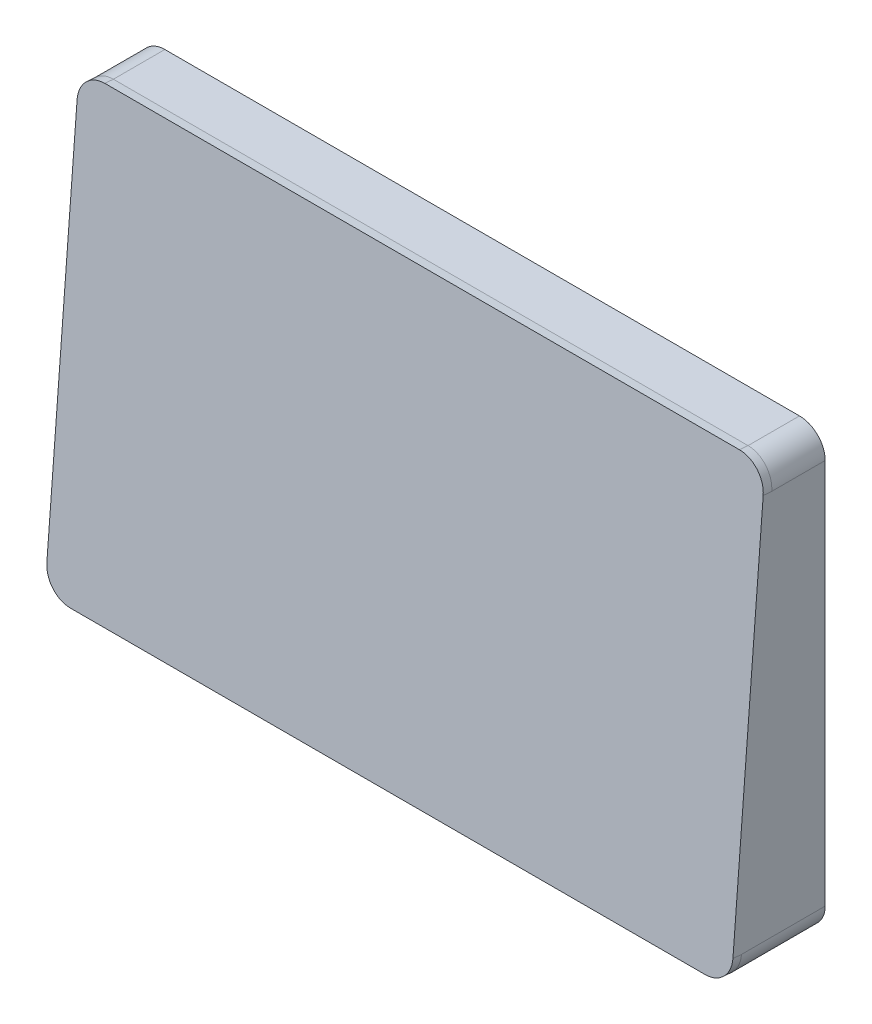
SolidWorks part; units mm, degrees
ref_plane "Front Plane" through (0, 0, 0) normal (0, 0, 1) x (1, 0, 0)
ref_plane "Top Plane" through (0, 0, 0) normal (0, 1, 0) x (1, 0, 0)
ref_plane "Right Plane" through (0, 0, 0) normal (1, 0, 0) x (0, 0, -1)
sketch "Sketch1" plane through (0, 0, 0) normal (0, 0, 1) x (1, 0, 0)
  line L0 (3.325, 90.1) -> (3.325, 0.1) construction
  line L1 (0.325, -2.9) -> (-147.675, -2.9) construction
  line L2 (-150.675, 0.1) -> (-150.675, 90.1) construction
  line L3 (-147.675, 93.1) -> (0.325, 93.1) construction
  line L4 (3.325, 90.1) -> (3.325, 0.1)
  line L5 (0.325, -2.9) -> (-147.675, -2.9)
  line L6 (-150.675, 0.1) -> (-150.675, 90.1)
  line L7 (-147.675, 93.1) -> (0.325, 93.1)
  line L8 (-153.675, 0.1) -> (-153.675, 90.1)
  line L9 (0.325, -5.9) -> (-147.675, -5.9)
  line L10 (6.325, 90.1) -> (6.325, 0.1)
  line L11 (-147.675, 96.1) -> (0.325, 96.1)
  arc A0 (3.325, 90.1) -> (0.325, 93.1) centre (0.325, 90.1) ccw construction
  arc A1 (0.325, -2.9) -> (3.325, 0.1) centre (0.325, 0.1) ccw construction
  arc A2 (-150.675, 0.1) -> (-147.675, -2.9) centre (-147.675, 0.1) ccw construction
  arc A3 (-147.675, 93.1) -> (-150.675, 90.1) centre (-147.675, 90.1) ccw construction
  arc A4 (3.325, 90.1) -> (0.325, 93.1) centre (0.325, 90.1) ccw
  arc A5 (0.325, -2.9) -> (3.325, 0.1) centre (0.325, 0.1) ccw
  arc A6 (-150.675, 0.1) -> (-147.675, -2.9) centre (-147.675, 0.1) ccw
  arc A7 (-147.675, 93.1) -> (-150.675, 90.1) centre (-147.675, 90.1) ccw
  arc A8 (-147.675, 96.1) -> (-153.675, 90.1) centre (-147.675, 90.1) ccw
  arc A9 (-153.675, 0.1) -> (-147.675, -5.9) centre (-147.675, 0.1) ccw
  arc A10 (0.325, -5.9) -> (6.325, 0.1) centre (0.325, 0.1) ccw
  arc A11 (6.325, 90.1) -> (0.325, 96.1) centre (0.325, 90.1) ccw
  dimension "D1" = 3
extrude "Boss-Extrude1" add sketch "Sketch1" along normal blind 20
sketch "Sketch2" plane through (6.325, 0, 0) normal (1, 0, 0) x (0, 0, -1)
  line L0 (-20, 96.1) -> (-12, 96.1)
  line L1 (-20, 96.1) -> (0, 96.1) construction
  line L2 (-12, 96.1) -> (-20, -5.9)
  line L3 (-20, -5.9) -> (-20, 96.1)
  dimension "D1" = 12
extrude "Cut-Extrude1" cut sketch "Sketch2" against normal through all
sketch "Sketch3" plane through (0, 1.523, 19.4178) normal (0, 0.0782, 0.9969) x (1, 0, 0)
  line L4 (-153.675, 88.8491) -> (-153.675, -1.4273)
  line L5 (-147.675, -7.4458) -> (0.325, -7.4458)
  line L6 (6.325, -1.4273) -> (6.325, 88.8491)
  line L7 (0.325, 94.8675) -> (-147.675, 94.8675)
  line L8 (-153.675, 88.8491) -> (-153.675, -1.4273)
  line L9 (-147.675, -7.4458) -> (0.325, -7.4458)
  line L10 (6.325, -1.4273) -> (6.325, 88.8491)
  line L11 (0.325, 94.8675) -> (-147.675, 94.8675)
  ellipse E4 centre (-147.675, -1.4273) end of major axis (-147.675, 4.5911) minor radius 6 (-153.675, -1.4273) -> (-147.675, -7.4458) ccw
  ellipse E5 centre (0.325, -1.4273) end of major axis (0.325, 4.5911) minor radius 6 (0.325, -7.4458) -> (6.325, -1.4273) ccw
  ellipse E6 centre (0.325, 88.8491) end of major axis (0.325, 94.8675) minor radius 6 (6.325, 88.8491) -> (0.325, 94.8675) ccw
  ellipse E7 centre (-147.675, 88.8491) end of major axis (-147.675, 94.8675) minor radius 6 (-147.675, 94.8675) -> (-153.675, 88.8491) ccw
  ellipse E8 centre (-147.675, -1.4273) end of major axis (-147.675, 4.5911) minor radius 6 (-153.675, -1.4273) -> (-147.675, -7.4458) ccw
  ellipse E9 centre (0.325, -1.4273) end of major axis (0.325, 4.5911) minor radius 6 (0.325, -7.4458) -> (6.325, -1.4273) ccw
  ellipse E10 centre (0.325, 88.8491) end of major axis (0.325, 94.8675) minor radius 6 (6.325, 88.8491) -> (0.325, 94.8675) ccw
  ellipse E11 centre (-147.675, 88.8491) end of major axis (-147.675, 94.8675) minor radius 6 (-147.675, 94.8675) -> (-153.675, 88.8491) ccw
  dimension "D1" = 0
extrude "Boss-Extrude2" add sketch "Sketch3" along normal blind 2
sketch "Sketch4" plane through (0, -2.9, 0) normal (0, 1, 0) x (1, 0, 0)
  line L0 (-147.675, 0) -> (0.325, 0) construction
  line L1 (-135.675, -12.5) -> (-126.675, -12.5)
  line L2 (-135.675, -12.5) -> (-135.675, -8)
  line L3 (-135.675, -8) -> (-126.675, -8)
  line L4 (-126.675, -12.5) -> (-126.675, -8)
  line L5 (-153.675, -19.5294) -> (-153.675, 0) construction
  dimension "D1" = 9
  dimension "D2" = 4.5
  dimension "D3" = 8
  dimension "D4" = 18
extrude "Cut-Extrude2" cut sketch "Sketch4" against normal through all
sketch "Sketch5" plane through (0, -2.9, 0) normal (0, 1, 0) x (1, 0, 0)
  line L0 (-126.675, -10.25) -> (-9.675, -10.25) construction
  line L1 (-126.675, -12.5) -> (-126.675, -8) construction
  line L2 (6.325, -19.5294) -> (6.325, 0) construction
  circle A0 centre (-5.675, -10.25) radius 1
  circle A1 centre (-9.675, -10.25) radius 1
  point P5 (0, 0)
  dimension "D1" = 2
  dimension "D2" = 2
  dimension "D3" = 4
  dimension "D4" = 12
extrude "Cut-Extrude3" cut sketch "Sketch5" against normal through all
